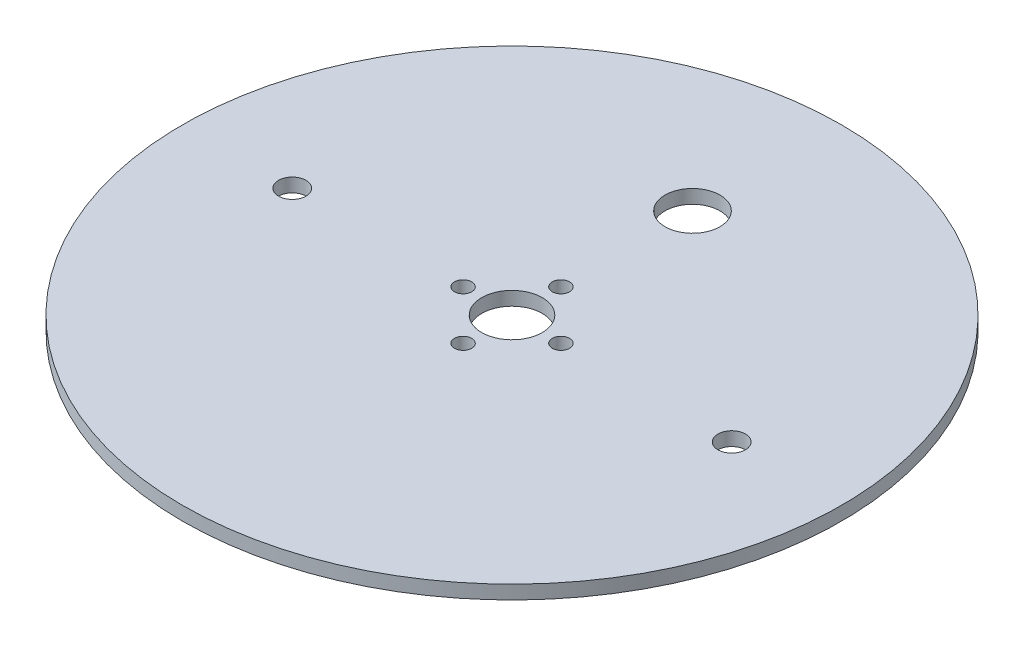
SolidWorks part; units mm, degrees
ref_plane "Front Plane" through (0, 0, 0) normal (0, 0, 1) x (1, 0, 0)
ref_plane "Top Plane" through (0, 0, 0) normal (0, 1, 0) x (1, 0, 0)
ref_plane "Right Plane" through (0, 0, 0) normal (1, 0, 0) x (0, 0, -1)
sketch "Sketch1" plane through (0, 0, 0) normal (0, 1, 0) x (1, 0, 0)
  circle A0 centre (0, 0) radius 76.2
  dimension "D1" = 152.4
extrude "Boss-Extrude1" add sketch "Sketch1" along normal blind 3.175
sketch "Sketch2" plane through (0, 3.175, 0) normal (0, 1, 0) x (1, 0, 0)
  circle A0 centre (0, 0) radius 7
  dimension "D1" = 14
extrude "Cut-Extrude1" cut sketch "Sketch2" against normal through all
sketch "Sketch3" plane through (0, 3.175, 0) normal (0, 1, 0) x (1, 0, 0)
  circle A0 centre (11.314, 0) radius 2
  circle A1 centre (0, -11.314) radius 2
  circle A2 centre (-11.314, 0) radius 2
  circle A3 centre (0, 11.314) radius 2
  point P12 (0, 0)
  dimension "D1" = 11.314
  dimension "D2" = 4
  dimension "D3" = 4
extrude "Cut-Extrude2" cut sketch "Sketch3" against normal through all
sketch "Sketch4" plane through (0, 0, 0) normal (0, -1, 0) x (1, 0, 0)
  circle A0 centre (-50.8, 0) radius 3.175 construction
  circle A1 centre (50.8, 0) radius 3.175 construction
  circle A2 centre (-50.8, 0) radius 3.175
  circle A3 centre (50.8, 0) radius 3.175
extrude "Cut-Extrude3" cut sketch "Sketch4" against normal through all
sketch "Sketch5" plane through (0, 3.175, 0) normal (0, 1, 0) x (1, 0, 0)
  circle A0 centre (0, 41.7338) radius 6.35 construction
  circle A1 centre (0, 41.7338) radius 6.35
extrude "Cut-Extrude4" cut sketch "Sketch5" against normal up to next
